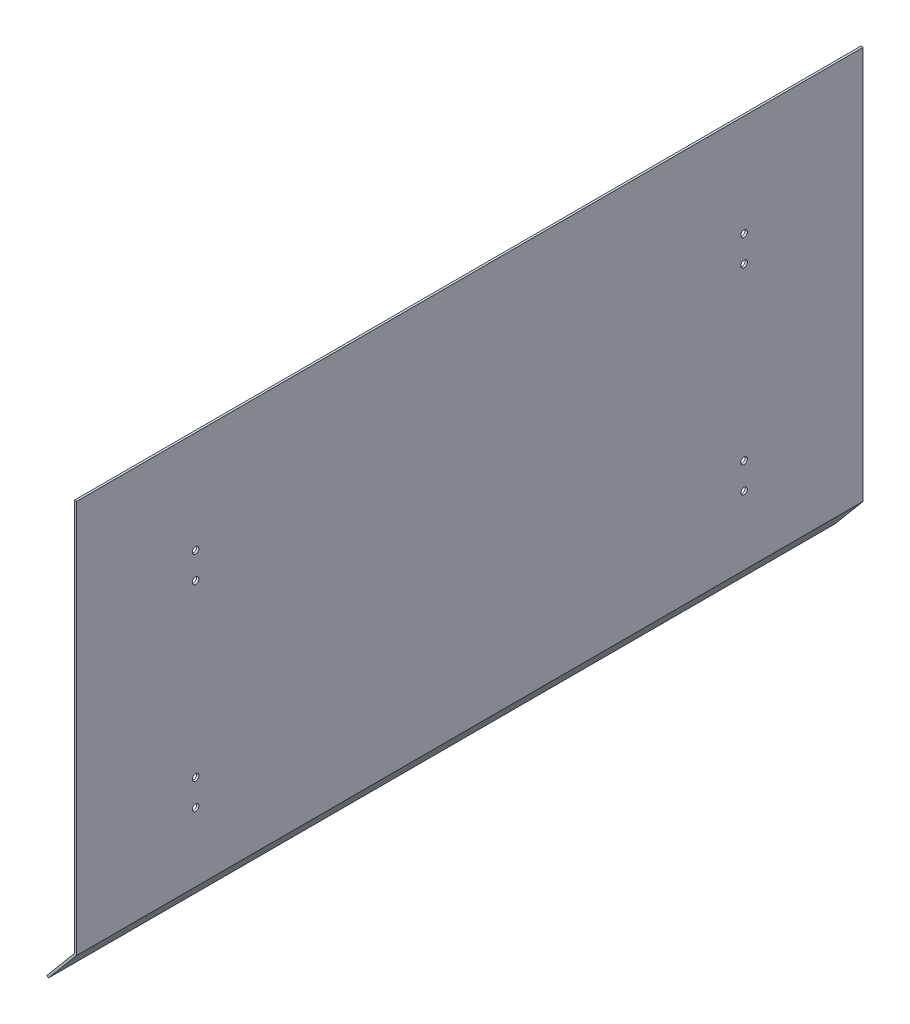
SolidWorks part; units mm, degrees
ref_plane "前视基准面" through (0, 0, 0) normal (0, 0, 1) x (1, 0, 0)
ref_plane "上视基准面" through (0, 0, 0) normal (0, 1, 0) x (1, 0, 0)
ref_plane "右视基准面" through (0, 0, 0) normal (1, 0, 0) x (0, 0, -1)
sketch "草图1" plane through (0, 0, 0) normal (0, 0, 1) x (1, 0, 0)
  line L0 (0, 0) -> (0, 180)
  line L1 (0, 0) -> (-12.8558, -15.3209)
  line L2 (-1, 0.364) -> (-13.6218, -14.6781)
  line L3 (-1, 0.364) -> (-1, 180)
  line L4 (-13.6218, -14.6781) -> (-12.8558, -15.3209)
  line L5 (-1, 180) -> (0, 180)
  dimension "D1" = 180
  dimension "D2" = 20
  dimension "D3" = 140
  dimension "D4" = 1
extrude "凸台-拉伸1" add sketch "草图1" along normal blind 360
sketch "草图2" plane through (-1, 0, 0) normal (-1, 0, 0) x (0, 0, 1)
  line L0 (360, 0.364) -> (0, 0.364) construction
  line L1 (360, 180) -> (360, 0.364) construction
  line L2 (180, 180) -> (180, -14.6781) construction
  line L3 (360, 180) -> (0, 180) construction
  line L4 (360, -14.6781) -> (0, -14.6781) construction
  circle A0 centre (305.5, 31.364) radius 1.5
  circle A1 centre (305.5, 43.364) radius 1.5
  circle A2 centre (305.5, 121.364) radius 1.5
  circle A3 centre (305.5, 133.364) radius 1.5
  circle A4 centre (54.5, 121.364) radius 1.5
  circle A5 centre (54.5, 31.364) radius 1.5
  circle A6 centre (54.5, 43.364) radius 1.5
  circle A7 centre (54.5, 133.364) radius 1.5
  dimension "D6" = 3
  dimension "D1" = 12
  dimension "D2" = 12
  dimension "D3" = 31
  dimension "D4" = 78
  dimension "D5" = 54.5
extrude "切除-拉伸1" cut sketch "草图2" against normal blind 380
